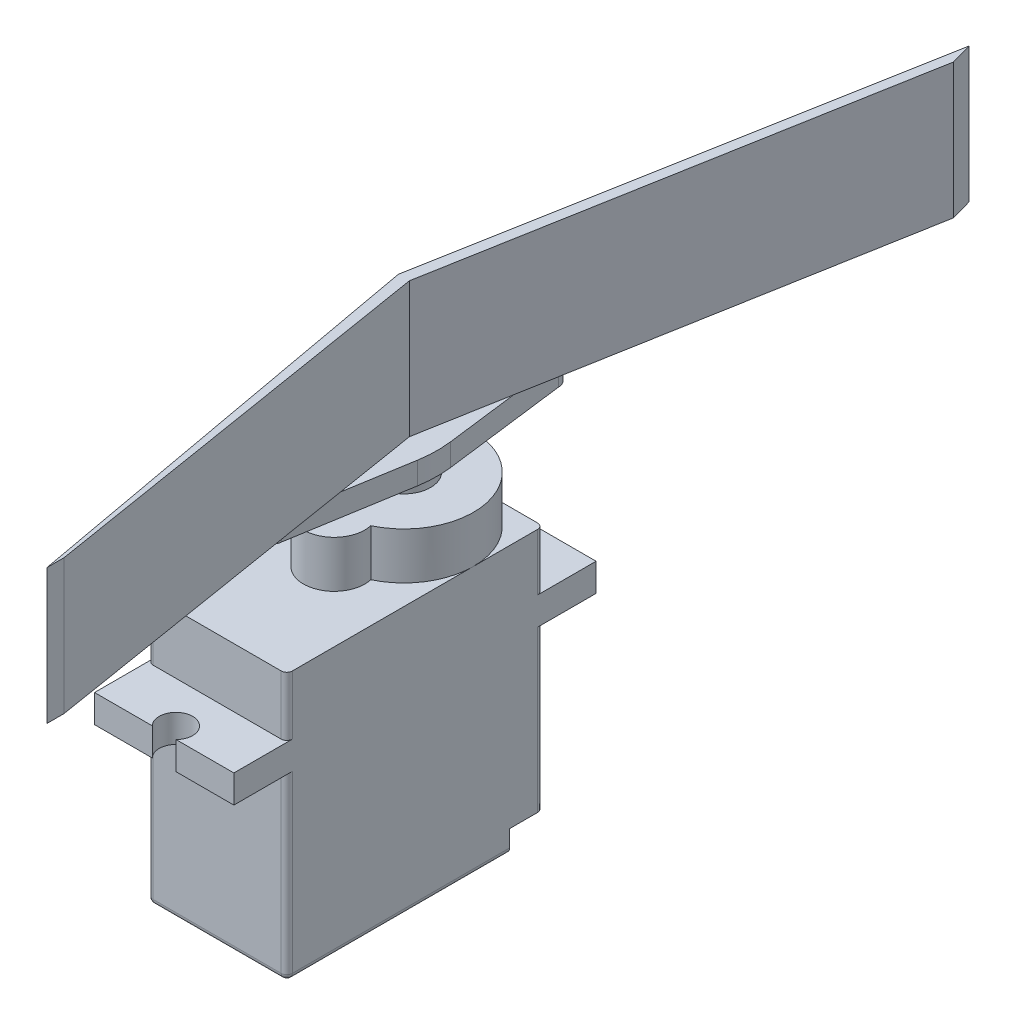
SolidWorks part; units mm, degrees
ref_plane "Front Plane" through (0, 0, 0) normal (0, 0, 1) x (1, 0, 0)
ref_plane "Top Plane" through (0, 0, 0) normal (0, 1, 0) x (1, 0, 0)
ref_plane "Right Plane" through (0, 0, 0) normal (1, 0, 0) x (0, 0, -1)
sketch "Sketch1" plane through (0, 0, 0) normal (0, 1, 0) x (1, 0, 0)
  line L0 (-6.25, 11.5) -> (6.25, -11.5) construction
  line L1 (-6.25, 11.5) -> (6.25, 11.5)
  line L2 (-6.25, 11.5) -> (-6.25, -11.5)
  line L3 (-6.25, -11.5) -> (6.25, -11.5)
  line L4 (6.25, 11.5) -> (6.25, -11.5)
  line L5 (6.25, 11.5) -> (-6.25, -11.5) construction
  point P7 (0, 0)
  dimension "D1" = 23
  dimension "D2" = 12.5
extrude "Boss-Extrude1" add sketch "Sketch1" along normal blind 24
sketch "Sketch2" plane through (0, 24, 0) normal (0, 1, 0) x (1, 0, 0)
  line L0 (6.25, -11.5) -> (6.25, 11.5) construction
  line L1 (6.25, 11.5) -> (-6.25, 11.5) construction
  line L2 (-6.25, 11.5) -> (-6.25, -11.5) construction
  line L3 (6.25, -11.5) -> (6.25, 11.5) construction
  line L4 (6.25, 11.5) -> (-6.25, 11.5) construction
  line L5 (-6.25, 11.5) -> (-6.25, -11.5) construction
  arc A0 (2.6826, -0.395) -> (-2.6826, -0.395) centre (0, 5.25) ccw
  arc A1 (-2.6826, -0.395) -> (2.6826, -0.395) centre (0, -1) ccw
  dimension "D1" = 5.5
extrude "Boss-Extrude2" add sketch "Sketch2" along normal blind 4.2 contours A0 A1
sketch "Sketch3" plane through (0, 28.2, 0) normal (0, 1, 0) x (1, 0, 0)
  arc A0 (2.6826, -0.395) -> (-2.6826, -0.395) centre (0, 5.25) ccw construction
  arc A1 (2.6826, -0.395) -> (-2.6826, -0.395) centre (0, 5.25) ccw construction
  circle A2 centre (0, 5.25) radius 2.4
  circle A3 centre (0, 5.25) radius 0.5
  dimension "D1" = 4.8
  dimension "D2" = 1
extrude "Boss-Extrude3" add sketch "Sketch3" along normal blind 3
sketch "Sketch4" plane through (0, 0, -11.5) normal (0, 0, -1) x (-1, 0, 0)
  line L0 (6.25, 24) -> (6.25, 0) construction
  line L1 (-6.25, 24) -> (-6.25, 0) construction
  line L2 (6.25, 24) -> (6.25, 0) construction
  line L3 (-6.25, 24) -> (-6.25, 0) construction
  line L5 (-6.25, 18.9) -> (6.25, 18.9)
  line L6 (-6.25, 18.9) -> (-6.25, 16.4)
  line L7 (-6.25, 16.4) -> (6.25, 16.4)
  line L8 (6.25, 18.9) -> (6.25, 16.4)
  dimension "D1" = 16.4
  dimension "D2" = 2.5
extrude "Boss-Extrude4" add sketch "Sketch4" along normal blind 4.75
sketch "Sketch5" plane through (0, 0, 11.5) normal (0, 0, 1) x (1, 0, 0)
  line L0 (-6.25, 24) -> (-6.25, 0) construction
  line L1 (6.25, 24) -> (6.25, 0) construction
  line L2 (-6.25, 24) -> (-6.25, 0) construction
  line L3 (6.25, 24) -> (6.25, 0) construction
  line L5 (6.25, 16.2) -> (-6.25, 16.2)
  line L6 (6.25, 16.2) -> (6.25, 18.7)
  line L7 (6.25, 18.7) -> (-6.25, 18.7)
  line L8 (-6.25, 16.2) -> (-6.25, 18.7)
  dimension "D1" = 16.2
  dimension "D2" = 2.5
extrude "Boss-Extrude5" add sketch "Sketch5" along normal blind 4.75
sketch "Sketch6" plane through (0, 18.7, 0) normal (0, 1, 0) x (1, 0, 0)
  line L0 (0, -16.25) -> (0, -11.5) construction
  line L10 (6.25, -11.5) -> (-6.25, -11.5) construction
  line L11 (6.25, -16.25) -> (6.25, -11.5) construction
  line L12 (-6.25, -16.25) -> (-6.25, -11.5) construction
  line L13 (6.25, -16.25) -> (-6.25, -16.25) construction
  line L14 (6.25, -11.5) -> (-6.25, -11.5) construction
  line L15 (6.25, -16.25) -> (6.25, -11.5) construction
  line L16 (-6.25, -16.25) -> (-6.25, -11.5) construction
  line L17 (6.25, -16.25) -> (-6.25, -16.25) construction
  circle A0 centre (0, -15.2) radius 1.5
  dimension "D1" = 3
  dimension "D2" = 3.7
extrude "Cut-Extrude1" cut sketch "Sketch6" against normal up to next
sketch "Sketch8" plane through (0, 18.9, 0) normal (0, 1, 0) x (1, 0, 0)
  line L0 (-6.25, 16.25) -> (6.25, 16.25) construction
  line L1 (-6.25, 16.25) -> (-6.25, 11.5) construction
  line L2 (-6.25, 11.5) -> (6.25, 11.5) construction
  line L3 (6.25, 16.25) -> (6.25, 11.5) construction
  line L4 (-6.25, 16.25) -> (6.25, 16.25) construction
  line L5 (-6.25, 16.25) -> (-6.25, 11.5) construction
  line L6 (-6.25, 11.5) -> (6.25, 11.5) construction
  line L7 (6.25, 16.25) -> (6.25, 11.5) construction
  line L8 (0, 16.25) -> (0, 11.5) construction
  circle A0 centre (0, 15.2) radius 1.5
  dimension "D1" = 3
  dimension "D2" = 3.7
extrude "Cut-Extrude2" cut sketch "Sketch8" against normal up to next contours A0
sketch "Sketch9" plane through (6.25, 0, 0) normal (1, 0, 0) x (0, 0, -1)
  line L0 (11.5, 2) -> (8.5, 0)
  line L1 (11.5, 16.4) -> (11.5, 0) construction
  line L2 (-11.5, 0) -> (11.5, 0) construction
  line L3 (8.5, 0) -> (11.5, 0)
  line L4 (11.5, 0) -> (11.5, 2)
  line L5 (11.5, 2) -> (8.5, 2) construction
  line L6 (8.5, 2) -> (8.5, 0) construction
  dimension "D1" = 2
  dimension "3" = 3
extrude "Cut-Extrude4" cut sketch "Sketch9" against normal through all contours L0 L3 L4
sketch "Sketch10" plane through (6.25, 0, 0) normal (1, 0, 0) x (0, 0, -1)
  line L0 (11.5, 2) -> (8.5, 2)
  line L1 (8.5, 0) -> (8.5, 2)
  dimension "D1" = 3
extrude "Cut-Extrude6" cut sketch "Sketch10" against normal blind 2.3 and the other way through all flip side to cut
sketch "Sketch11" plane through (-6.25, 0, 0) normal (-1, 0, 0) x (0, 0, 1)
  line L0 (-11.5, 2) -> (-8.5, 2)
  line L1 (-8.5, 2) -> (-8.5, 0)
extrude "Cut-Extrude7" cut sketch "Sketch11" against normal blind 2.3 and the other way through all flip side to cut
fillet "Fillet1" radius 0.5 11 edges at (-6.25, 21.45, -11.5) (6.25, 21.45, -11.5) (-6.25, 21.35, 11.5) (0, 0, 11.5) (6.25, 0, 1.5) (-6.25, 0, 1.5) (6.25, 9.2, -11.5) (-6.25, 9.2, -11.5) (-6.25, 8.1, 11.5) (6.25, 8.1, 11.5) (6.25, 21.35, 11.5)
sketch "Croquis2" plane through (0, 31.2, 0) normal (0, 1, 0) x (1, 0, 0)
  line L0 (-2.9262, 5.25) -> (-0.8432, 17.8033)
  line L1 (1.3324, 17.8232) -> (2.9262, 5.25)
  line L2 (2.9262, 5.25) -> (0.9478, -6.6733)
  line L3 (-0.8348, -6.7724) -> (-2.9262, 5.25)
  circle A0 centre (0, 5.25) radius 2.9262
  arc A1 (-0.8544, 17.736) -> (1.3393, 17.7687) centre (0.2425, 17.7524) cw
  arc A2 (-0.8348, -6.7724) -> (0.9478, -6.6733) centre (0.0502, -6.61) ccw
  point P7 (0, 0)
  point P13 (0.9903, -6.66)
  point P14 (-0.8544, 17.736)
  point P15 (1.3393, 17.7524)
  point P18 (0, 0)
  point P19 (0, 0)
  point P20 (0, 0)
  point P21 (0, 0)
extrude "Saliente-Extruir2" add sketch "Croquis2" against normal blind 2
fillet "Redondeo1" radius 10 2 edges at (2.9262, 30.2, -5.25) (-2.9262, 30.2, -5.25)
sketch "Croquis3" plane through (0, 31.2, 0) normal (0, 1, 0) x (1, 0, 0)
  line L0 (-0.5, 5.25) -> (7.3628, 48.5995)
  line L1 (7.3628, 48.5995) -> (7.9045, 46.6493)
  line L2 (7.9045, 46.6493) -> (0.5, 5.25)
  line L3 (0.5, 5.25) -> (6.5216, -31.7533)
  line L4 (6.5216, -31.7533) -> (6.5216, -33.2897)
  line L5 (6.5216, -33.2897) -> (-0.5, 5.25)
  circle A0 centre (0, 5.25) radius 0.5 construction
  circle A1 centre (0, 5.25) radius 0.5 construction
  point P6 (7.3628, 48.5995)
  point P11 (7.9045, 46.6493)
extrude "Saliente-Extruir5" add sketch "Croquis3" along normal blind 12.1166 separate body
